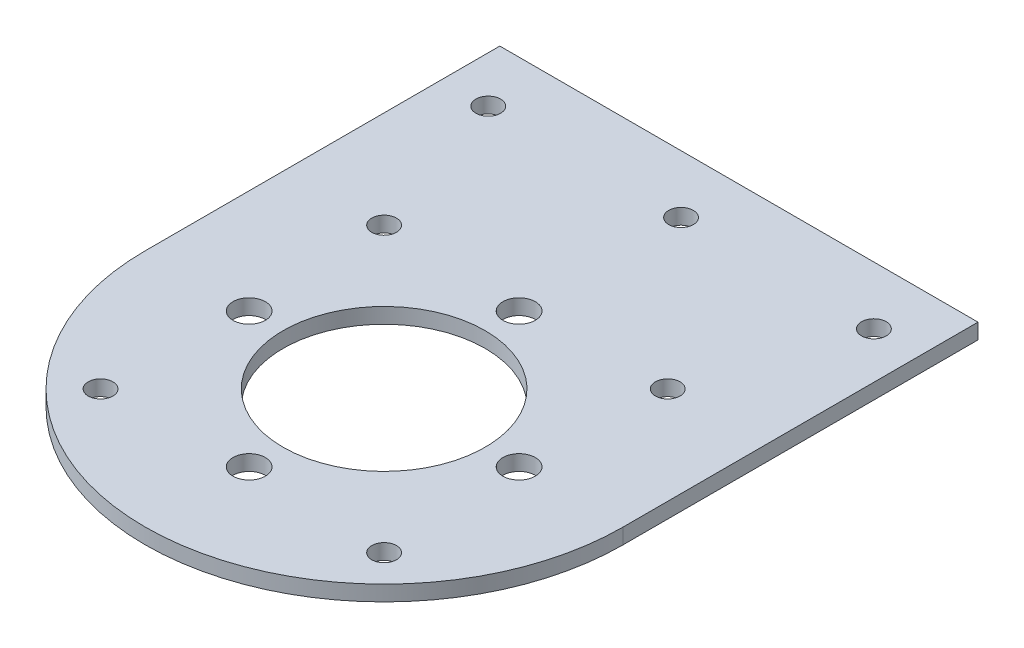
SolidWorks part; units mm, degrees
material "Thornel Mat VMA"
ref_plane "前视基准面" through (0, 0, 0) normal (0, 0, 1) x (1, 0, 0)
ref_plane "上视基准面" through (0, 0, 0) normal (0, 1, 0) x (1, 0, 0)
ref_plane "右视基准面" through (0, 0, 0) normal (1, 0, 0) x (0, 0, -1)
sketch "草图1" plane through (0, 0, 0) normal (0, 1, 0) x (1, 0, 0)
  line L0 (-31, 0) -> (-31, 31)
  line L1 (-31, 31) -> (31, 31) construction
  line L2 (31, 31) -> (31, 0)
  line L3 (-31, 31) -> (-31, 46)
  line L4 (-31, 46) -> (31, 46)
  line L5 (31, 46) -> (31, 31)
  line L6 (-31, 38.5) -> (-25, 38.5) construction
  line L7 (-25, 38.5) -> (0, 38.5) construction
  line L8 (0, 38.5) -> (25, 38.5) construction
  line L9 (25, 38.5) -> (31, 38.5) construction
  line L10 (0, 0) -> (0, 26) construction
  line L11 (0, 0) -> (18.3848, 18.3848) construction
  circle A0 centre (0, 0) radius 31
  circle A1 centre (0, 0) radius 21
  circle A2 centre (0, 0) radius 13.1
  circle A3 centre (0, 0) radius 17.5 construction
  circle A4 centre (0, 17.5) radius 2.1
  circle A5 centre (-17.5, 0) radius 2.1
  circle A6 centre (0, -17.5) radius 2.1
  circle A7 centre (17.5, 0) radius 2.1
  circle A8 centre (-25, 38.5) radius 1.6
  circle A9 centre (0, 38.5) radius 1.6
  circle A10 centre (25, 38.5) radius 1.6
  circle A11 centre (0, 0) radius 26 construction
  circle A12 centre (18.3848, 18.3848) radius 1.6
  circle A13 centre (18.3848, -18.3848) radius 1.6
  circle A14 centre (-18.3848, -18.3848) radius 1.6
  circle A15 centre (-18.3848, 18.3848) radius 1.6
  dimension "D3" = 42
  dimension "D4" = 26.2
  dimension "D5" = 35
  dimension "D6" = 4.2
  dimension "D8" = 3.2
  dimension "D9" = 52
  dimension "D1" = 31
  dimension "D2" = 15
  dimension "D7" = 6
  dimension "D10" = 45
  dimension "D11" = 4
extrude "凸台-拉伸1" add sketch "草图1" along normal blind 2 contours A0 L2 L5 L4 L3 L0 A10 A9 A8 | A0 A15 A14 A13 A12 A1 | A1 A7 A6 A5 A4 A2
